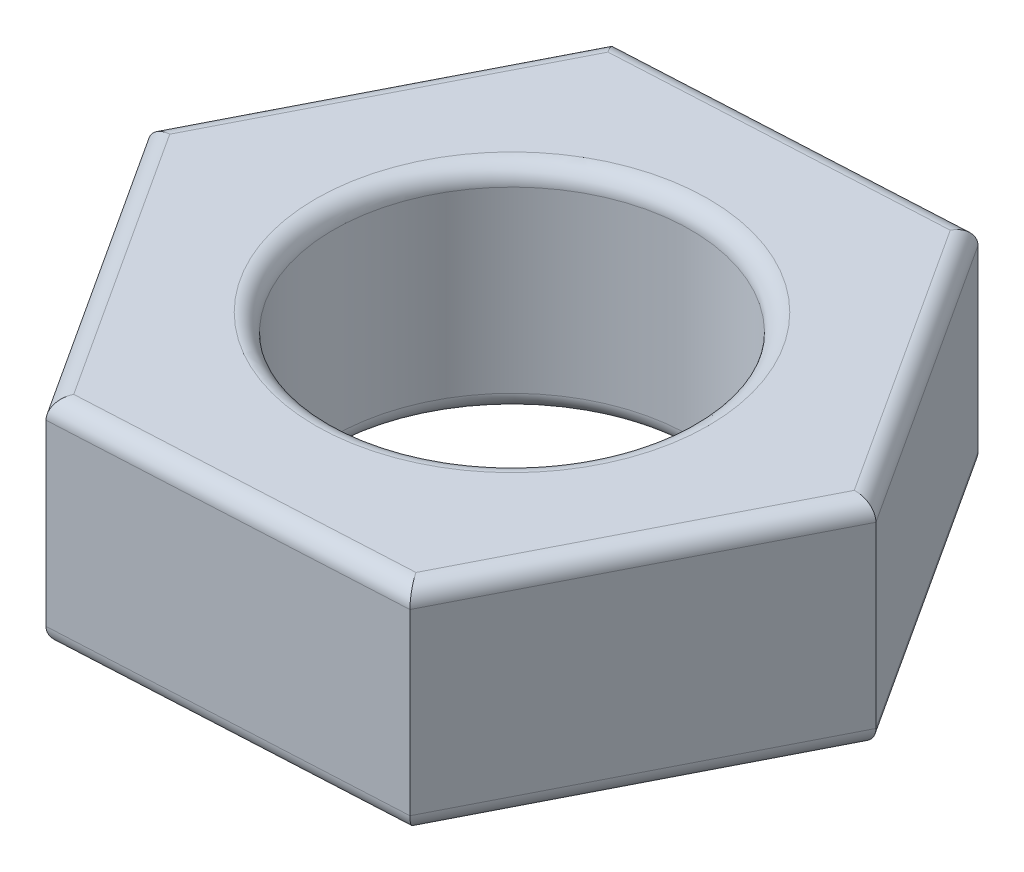
SolidWorks part; units mm, degrees
material "Chrome Stainless Steel"
ref_plane "Front Plane" through (0, 0, 0) normal (0, 0, 1) x (1, 0, 0)
ref_plane "Top Plane" through (0, 0, 0) normal (0, 1, 0) x (1, 0, 0)
ref_plane "Right Plane" through (0, 0, 0) normal (1, 0, 0) x (0, 0, -1)
sketch "Sketch1" plane through (0, 0, 0) normal (0, 1, 0) x (1, 0, 0)
  line L1 (5.2793, -8.1369) -> (9.6864, 0.5036)
  line L2 (9.6864, 0.5036) -> (4.4071, 8.6405)
  line L3 (4.4071, 8.6405) -> (-5.2793, 8.1369)
  line L4 (-5.2793, 8.1369) -> (-9.6864, -0.5036)
  line L5 (-9.6864, -0.5036) -> (-4.4071, -8.6405)
  line L6 (-4.4071, -8.6405) -> (5.2793, -8.1369)
  circle A0 centre (0, 0) radius 8.4 construction
  circle A1 centre (0, 0) radius 5
  dimension "D2" = 10
  dimension "D1" = 16.8
extrude "Boss-Extrude1" add sketch "Sketch1" along normal blind 6
fillet "Fillet1" radius 0.5 14 edges at (0, 0, 5) (7.4828, 0, 3.8167) (7.0468, 0, -4.572) (-0.4361, 0, -8.3887) (-7.4828, 0, -3.8167) (-7.0468, 0, 4.572) (0.4361, 0, 8.3887) (0, 6, 5) (-7.0468, 6, 4.572) (-7.4828, 6, -3.8167) (-0.4361, 6, -8.3887) (7.0468, 6, -4.572) (7.4828, 6, 3.8167) (0.4361, 6, 8.3887)
